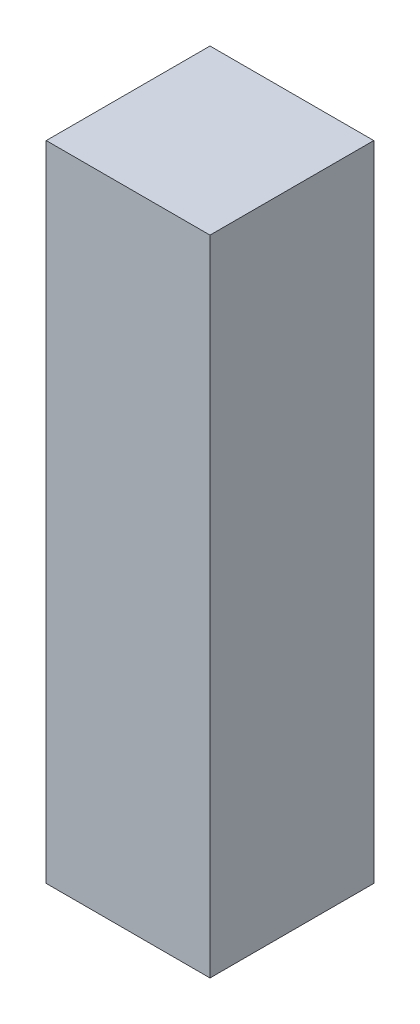
SolidWorks part; units mm, degrees
material "Balsa"
ref_plane "Alzado" through (0, 0, 0) normal (0, 0, 1) x (1, 0, 0)
ref_plane "Planta" through (0, 0, 0) normal (0, 1, 0) x (1, 0, 0)
ref_plane "Vista lateral" through (0, 0, 0) normal (1, 0, 0) x (0, 0, -1)
sketch "Croquis1" plane through (0, 0, 0) normal (0, 1, 0) x (1, 0, 0)
  line L1 (-3.5, -3.5) -> (3.5, -3.5)
  line L2 (-3.5, -3.5) -> (-3.5, 3.5)
  line L3 (-3.5, 3.5) -> (3.5, 3.5)
  line L4 (3.5, -3.5) -> (3.5, 3.5)
  line L5 (-3.5, -3.5) -> (3.5, 3.5) construction
  line L6 (-3.5, 3.5) -> (3.5, -3.5) construction
  point P0 (0, 0)
  dimension "D1" = 7
  dimension "D2" = 7
extrude "Saliente-Extruir1" add sketch "Croquis1" along normal mid plane 27.5
